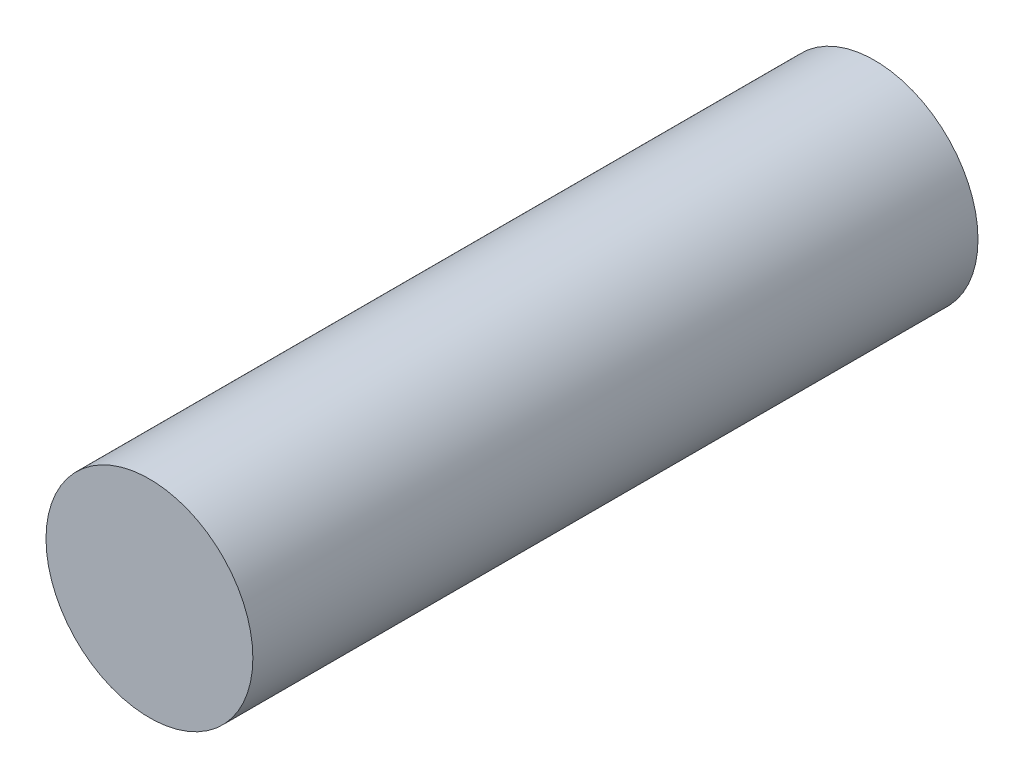
SolidWorks part; units mm, degrees
ref_plane "Front Plane" through (0, 0, 0) normal (0, 0, 1) x (1, 0, 0)
ref_plane "Top Plane" through (0, 0, 0) normal (0, 1, 0) x (1, 0, 0)
ref_plane "Right Plane" through (0, 0, 0) normal (1, 0, 0) x (0, 0, -1)
other "Центр тяжести"
sketch "Эскиз1" plane through (0, 0, 0) normal (0, 0, 1) x (1, 0, 0)
  circle A0 centre (0, 0) radius 9.3
  dimension "D1" = 18.6
extrude "Бобышка-Вытянуть1" add sketch "Эскиз1" along normal mid plane 65.2
